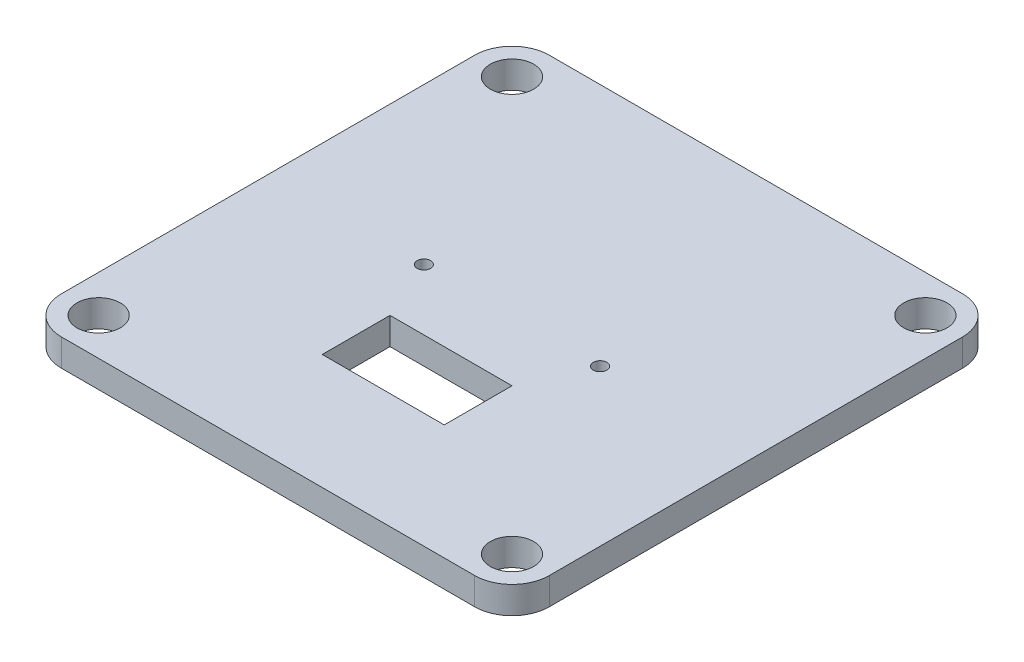
SolidWorks part; units mm, degrees
ref_plane "前视基准面" through (0, 0, 0) normal (0, 0, 1) x (1, 0, 0)
ref_plane "上视基准面" through (0, 0, 0) normal (0, 1, 0) x (1, 0, 0)
ref_plane "右视基准面" through (0, 0, 0) normal (1, 0, 0) x (0, 0, -1)
other "Configuration Table"
sketch "草图1" plane through (0, 0, 0) normal (0, 1, 0) x (1, 0, 0)
  line L0 (-18, 0) -> (18, 0) construction
  line L1 (-15.25, -18) -> (15.25, -18)
  line L2 (-18, -15.25) -> (-18, 15.25)
  line L3 (-15.25, 18) -> (15.25, 18)
  line L4 (18, -15.25) -> (18, 15.25)
  line L5 (-18, -18) -> (18, 18) construction
  line L6 (-18, 18) -> (18, -18) construction
  line L7 (0, -18) -> (0, 18) construction
  line L8 (-4.5, -4.5) -> (4.5, -4.5)
  line L9 (-4.5, -4.5) -> (-4.5, -9.5)
  line L10 (-4.5, -9.5) -> (4.5, -9.5)
  line L11 (4.5, -4.5) -> (4.5, -9.5)
  circle A0 centre (15.25, 15.25) radius 1.6
  circle A1 centre (15.25, -15.25) radius 1.6
  circle A2 centre (-15.25, -15.25) radius 1.6
  circle A3 centre (-15.25, 15.25) radius 1.6
  arc A4 (15.25, -18) -> (18, -15.25) centre (15.25, -15.25) ccw
  arc A5 (15.25, 18) -> (18, 15.25) centre (15.25, 15.25) cw
  arc A6 (-18, 15.25) -> (-15.25, 18) centre (-15.25, 15.25) cw
  arc A7 (-15.25, -18) -> (-18, -15.25) centre (-15.25, -15.25) cw
  circle A8 centre (-6.5, 0) radius 0.5
  circle A9 centre (6.5, 0) radius 0.5
  point P0 (0, 0)
  point P9 (0, 0)
  point P12 (0, 0)
  point P23 (0, 0)
  dimension "D3" = 3.2
  dimension "D6" = 2.75
  dimension "D7" = 1
  dimension "D9" = 9.5
  dimension "D1" = 36
  dimension "D2" = 36
  dimension "D4" = 15.25
  dimension "D8" = 13
  dimension "D10" = 5
  dimension "D11" = 9
  dimension "D5" = 4
extrude "凸台-拉伸1" add sketch "草图1" along normal blind 2
